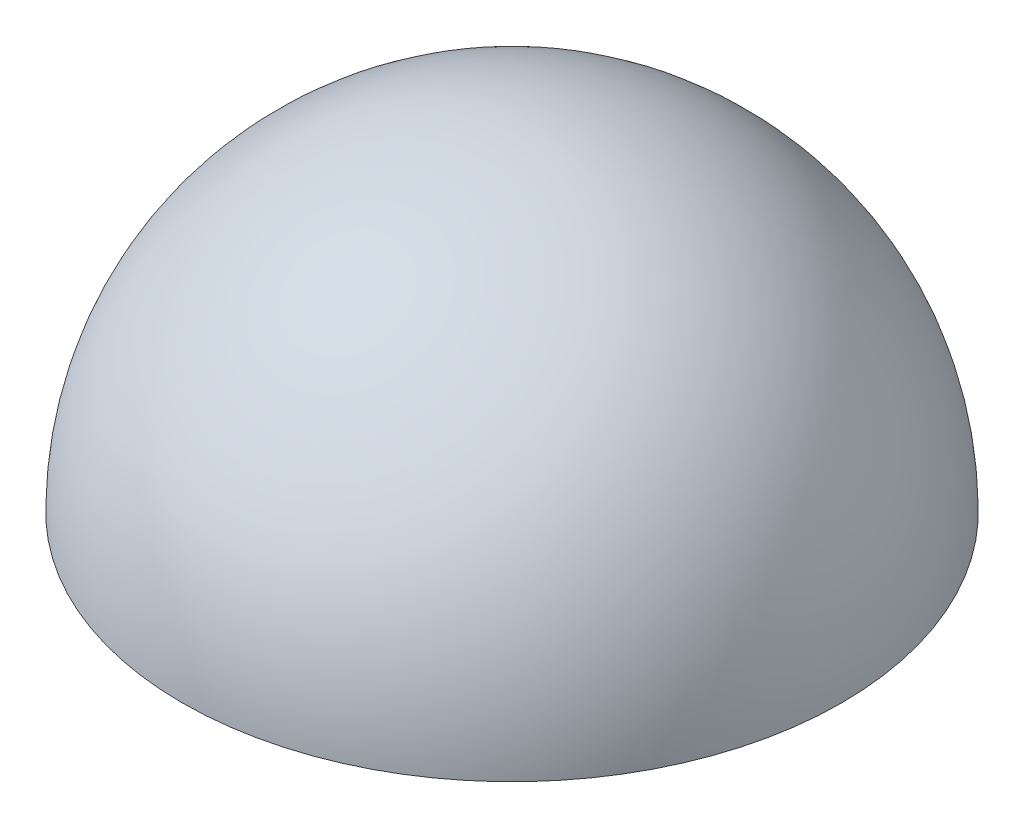
SolidWorks part; units mm, degrees
ref_plane "Front Plane" through (0, 0, 0) normal (0, 0, 1) x (1, 0, 0)
ref_plane "Top Plane" through (0, 0, 0) normal (0, 1, 0) x (1, 0, 0)
ref_plane "Right Plane" through (0, 0, 0) normal (1, 0, 0) x (0, 0, -1)
sketch "Sketch1" plane through (0, 0, 0) normal (0, 0, 1) x (1, 0, 0)
  line L0 (0, 298.45) -> (0, 0) construction
  line L1 (0, 294.386) -> (0, 298.45)
  line L2 (-298.45, 0) -> (-294.386, 0)
  line L3 (0, 0) -> (-298.45, 0) construction
  arc A0 (0, 294.386) -> (-294.386, 0) centre (0, 0) ccw
  arc A1 (0, 298.45) -> (-298.45, 0) centre (0, 0) ccw
  dimension "D1" = 596.9
  dimension "D2" = 4.064
revolve "Revolve1" add sketch "Sketch1" angle 360 about L0
